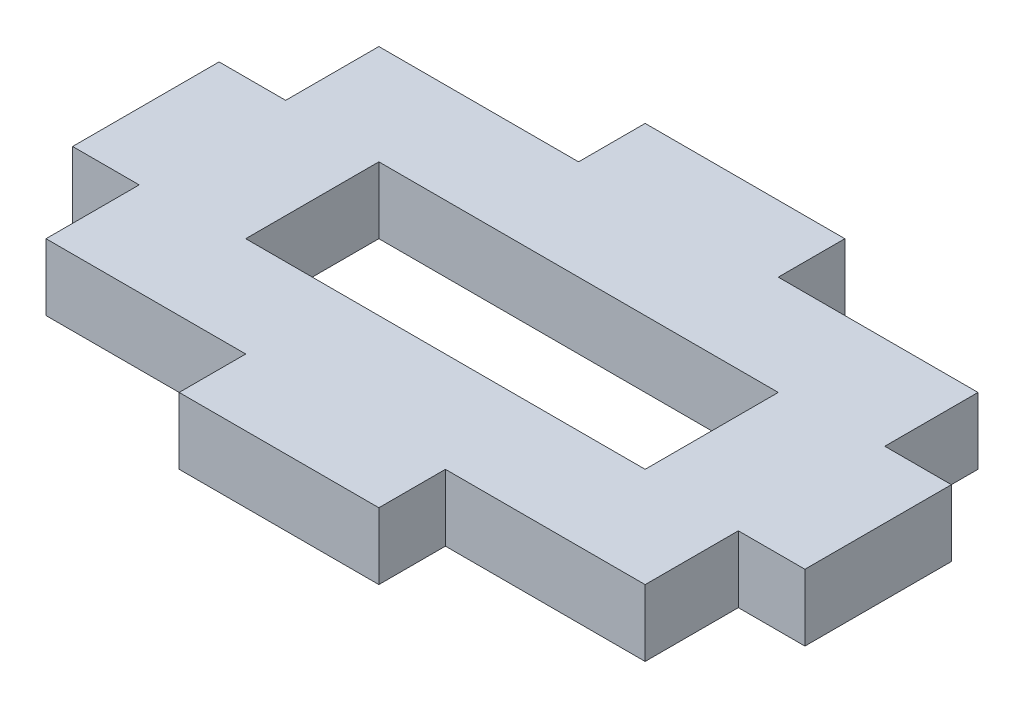
SolidWorks part; units mm, degrees
ref_plane "Front Plane" through (0, 0, 0) normal (0, 0, 1) x (1, 0, 0)
ref_plane "Top Plane" through (0, 0, 0) normal (0, 1, 0) x (1, 0, 0)
ref_plane "Right Plane" through (0, 0, 0) normal (1, 0, 0) x (0, 0, -1)
sketch "Sketch1" plane through (0, 0, 0) normal (0, 1, 0) x (1, 0, 0)
  line L0 (-11.3454, 0) -> (12.5059, 0) construction
  line L1 (-22.5, -12.5) -> (-7.5, -12.5)
  line L2 (-22.5, -12.5) -> (-22.5, -5.5)
  line L3 (-22.5, 12.5) -> (-7.5, 12.5)
  line L4 (22.5, -12.5) -> (22.5, -5.5)
  line L5 (-22.5, -12.5) -> (22.5, 12.5) construction
  line L6 (-22.5, 12.5) -> (22.5, -12.5) construction
  line L7 (0, 6.5897) -> (0, -5.5365) construction
  line L8 (7.5, -12.5) -> (22.5, -12.5)
  line L10 (-7.5, -12.5) -> (-7.5, -17.5)
  line L11 (-7.5, -17.5) -> (7.5, -17.5)
  line L12 (7.5, -12.5) -> (7.5, -17.5)
  line L13 (-7.5, 12.5) -> (-7.5, 17.5)
  line L14 (7.5, 12.5) -> (7.5, 17.5)
  line L15 (-7.5, 17.5) -> (7.5, 17.5)
  line L16 (7.5, 12.5) -> (22.5, 12.5)
  line L17 (-22.5, 5.5) -> (-22.5, 12.5)
  line L18 (-22.5, 5.5) -> (-27.5, 5.5)
  line L20 (-22.5, -5.5) -> (-27.5, -5.5)
  line L21 (-27.5, 5.5) -> (-27.5, -5.5)
  line L22 (22.5, -5.5) -> (27.5, -5.5)
  line L23 (27.5, 5.5) -> (27.5, -5.5)
  line L24 (22.5, 5.5) -> (27.5, 5.5)
  line L25 (22.5, 5.5) -> (22.5, 12.5)
  line L31 (-15, -5) -> (15, -5)
  line L32 (-15, -5) -> (-15, 5)
  line L33 (-15, 5) -> (15, 5)
  line L34 (15, -5) -> (15, 5)
  line L35 (-15, -5) -> (15, 5) construction
  line L36 (-15, 5) -> (15, -5) construction
  point P0 (0, 0)
  point P26 (0, 0.5266)
  point P27 (0, 0)
  dimension "D1" = 45
  dimension "D2" = 25
  dimension "D3" = 15
  dimension "D4" = 15
  dimension "D5" = 5
  dimension "D6" = 11
  dimension "D7" = 5
  dimension "D8" = 7
  dimension "D9" = 30
  dimension "D10" = 10
extrude "Boss-Extrude1" add sketch "Sketch1" along normal blind 5
